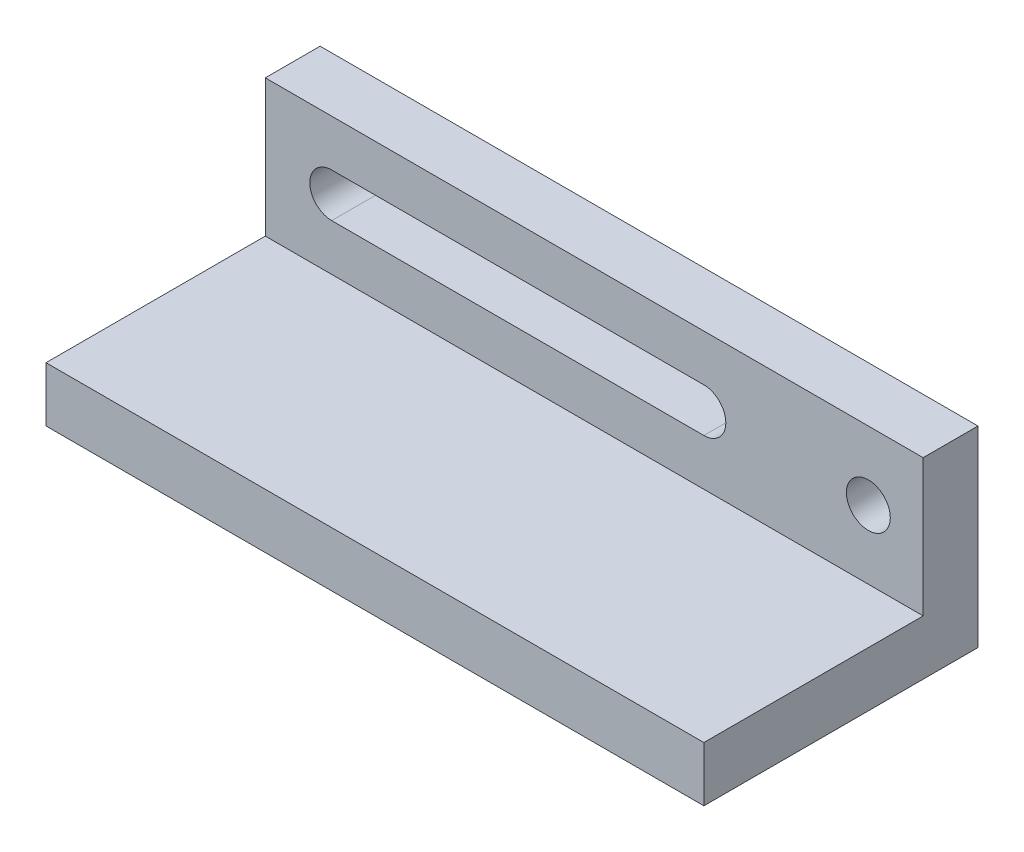
SolidWorks part; units mm, degrees
material "Nylon 101"
ref_plane "Front Plane" through (0, 0, 0) normal (0, 0, 1) x (1, 0, 0)
ref_plane "Top Plane" through (0, 0, 0) normal (0, 1, 0) x (1, 0, 0)
ref_plane "Right Plane" through (0, 0, 0) normal (1, 0, 0) x (0, 0, -1)
sketch "Sketch1" plane through (0, 0, 0) normal (0, 0, 1) x (1, 0, 0)
  line L0 (-47.89, 0) -> (20, 0) construction
  line L1 (-60, -12.5) -> (60, -12.5)
  line L2 (-60, -12.5) -> (-60, 12.5)
  line L3 (-60, 12.5) -> (60, 12.5)
  line L4 (60, -12.5) -> (60, 12.5)
  line L5 (-60, -12.5) -> (60, 12.5) construction
  line L6 (-60, 12.5) -> (60, -12.5) construction
  line L7 (-47.89, 4) -> (20, 4)
  line L8 (-47.89, -4) -> (20, -4)
  circle A0 centre (50, 0) radius 4
  arc A1 (-47.89, 4) -> (-47.89, -4) centre (-47.89, 0) ccw
  arc A2 (20, -4) -> (20, 4) centre (20, 0) ccw
  point P0 (0, 0)
  point P10 (-13.945, 0)
  dimension "D1" = 8
  dimension "D7" = 4
  dimension "D2" = 25
  dimension "D3" = 120
  dimension "D4" = 97.89
  dimension "D5" = 30
  dimension "D6" = 10
extrude "Boss-Extrude1" add sketch "Sketch1" along normal blind 10
sketch "Sketch2" plane through (0, 0, 0) normal (0, 0, -1) x (-1, 0, 0)
  line L0 (-60, -12.5) -> (-60, 12.5) construction
  line L1 (60, -12.5) -> (-60, -12.5)
  line L2 (60, -12.5) -> (60, -22.5)
  line L3 (60, -22.5) -> (-60, -22.5)
  line L4 (-60, -12.5) -> (-60, -22.5)
  dimension "D1" = 10
extrude "Boss-Extrude2" add sketch "Sketch2" against normal blind 50
